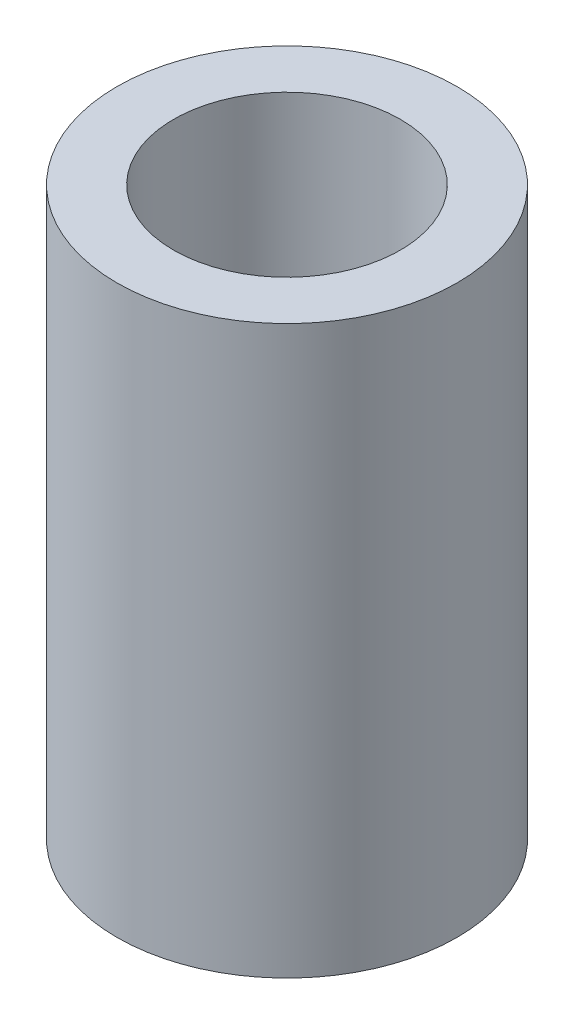
SolidWorks part; units mm, degrees
ref_plane "Plan de face" through (0, 0, 0) normal (0, 0, 1) x (1, 0, 0)
ref_plane "Plan de dessus" through (0, 0, 0) normal (0, 1, 0) x (1, 0, 0)
ref_plane "Plan de droite" through (0, 0, 0) normal (1, 0, 0) x (0, 0, -1)
sketch "Esquisse1" plane through (0, 0, 0) normal (0, 1, 0) x (1, 0, 0)
  circle A0 centre (0, 0) radius 2
  circle A1 centre (0, 0) radius 3
  dimension "D1" = 6
  dimension "D2" = 4
extrude "Extrusion1" add sketch "Esquisse1" along normal mid plane 10
